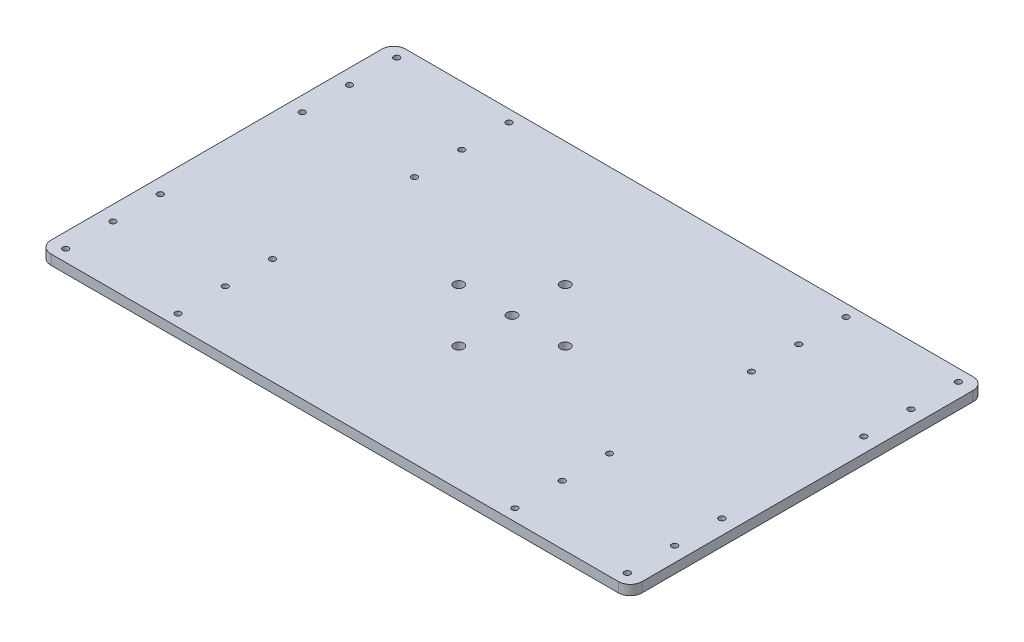
SolidWorks part; units mm, degrees
ref_plane "Front Plane" through (0, 0, 0) normal (0, 0, 1) x (1, 0, 0)
ref_plane "Top Plane" through (0, 0, 0) normal (0, 1, 0) x (1, 0, 0)
ref_plane "Right Plane" through (0, 0, 0) normal (1, 0, 0) x (0, 0, -1)
sketch "Sketch1" plane through (0, 0, 0) normal (0, 1, 0) x (1, 0, 0)
  line L0 (-142.5, 90) -> (-142.5, -90) construction
  line L1 (-144, -90) -> (144, -90)
  line L2 (-150, -84) -> (-150, 84)
  line L3 (-144, 90) -> (144, 90)
  line L4 (150, -84) -> (150, 84)
  line L5 (-150, -90) -> (150, 90) construction
  line L6 (-150, 90) -> (150, -90) construction
  line L7 (0, 0) -> (-30, -30) construction
  line L8 (0, 90) -> (0, -90) construction
  line L9 (-150, 0) -> (150, 0) construction
  line L10 (-9.5, -10) -> (9.5, -10) construction
  line L11 (-10, -9.5) -> (-10, 9.5) construction
  line L12 (-9.5, 10) -> (9.5, 10) construction
  line L13 (10, -9.5) -> (10, 9.5) construction
  line L14 (-10, -10) -> (10, 10) construction
  line L15 (-10, 10) -> (10, -10) construction
  circle A0 centre (-142.5, 84) radius 1.5
  circle A1 centre (-142.5, 60) radius 1.5
  circle A2 centre (-142.5, 36) radius 1.5
  circle A3 centre (-85.5, 84) radius 1.5
  circle A4 centre (-85.5, 60) radius 1.5
  circle A5 centre (-85.5, 36) radius 1.5
  circle A6 centre (85.5, 36) radius 1.5
  circle A7 centre (85.5, 60) radius 1.5
  circle A8 centre (85.5, 84) radius 1.5
  circle A9 centre (142.5, 36) radius 1.5
  circle A10 centre (142.5, 60) radius 1.5
  circle A11 centre (142.5, 84) radius 1.5
  circle A12 centre (142.5, -84) radius 1.5
  circle A13 centre (142.5, -60) radius 1.5
  circle A14 centre (142.5, -36) radius 1.5
  circle A15 centre (85.5, -84) radius 1.5
  circle A16 centre (85.5, -60) radius 1.5
  circle A17 centre (85.5, -36) radius 1.5
  circle A18 centre (-85.5, -36) radius 1.5
  circle A19 centre (-85.5, -60) radius 1.5
  circle A20 centre (-85.5, -84) radius 1.5
  circle A21 centre (-142.5, -36) radius 1.5
  circle A22 centre (-142.5, -60) radius 1.5
  circle A23 centre (-142.5, -84) radius 1.5
  arc A24 (9.5, 10) -> (10, 9.5) centre (9.5, 9.5) cw construction
  arc A25 (10, -9.5) -> (9.5, -10) centre (9.5, -9.5) cw construction
  arc A26 (-9.5, -10) -> (-10, -9.5) centre (-9.5, -9.5) cw construction
  arc A27 (-10, 9.5) -> (-9.5, 10) centre (-9.5, 9.5) cw construction
  circle A28 centre (0, 27) radius 2.5
  circle A29 centre (27, 0) radius 2.5
  circle A30 centre (0, -27) radius 2.5
  circle A31 centre (-27, 0) radius 2.5
  circle A32 centre (0, 0) radius 2.5
  circle A33 centre (-30, -30) radius 2.5 construction
  circle A34 centre (-30, 30) radius 2.5 construction
  circle A35 centre (30, 30) radius 2.5 construction
  circle A36 centre (30, -30) radius 2.5 construction
  arc A37 (144, 90) -> (150, 84) centre (144, 84) cw
  arc A38 (150, -84) -> (144, -90) centre (144, -84) cw
  arc A39 (-144, -90) -> (-150, -84) centre (-144, -84) cw
  arc A40 (-150, 84) -> (-144, 90) centre (-144, 84) cw
  point P0 (0, 0)
  point P59 (0, 0)
  point P88 (0, 0)
  point P98 (0, 0)
  dimension "D5" = 3
  dimension "D9" = 0.5
  dimension "D10" = 17
  dimension "D11" = 5
  dimension "D14" = 57
  dimension "D15" = 45
  dimension "D17" = 60
  dimension "D18" = 5
  dimension "D19" = 6
  dimension "D1" = 300
  dimension "D2" = 180
  dimension "D3" = 7.5
  dimension "D4" = 3
  dimension "D6" = 6
  dimension "D8" = 20
  dimension "D13" = 24
  dimension "D7" = 2
  dimension "D12" = 4
  dimension "D16" = 4
extrude "Boss-Extrude1" add sketch "Sketch1" along normal blind 5
